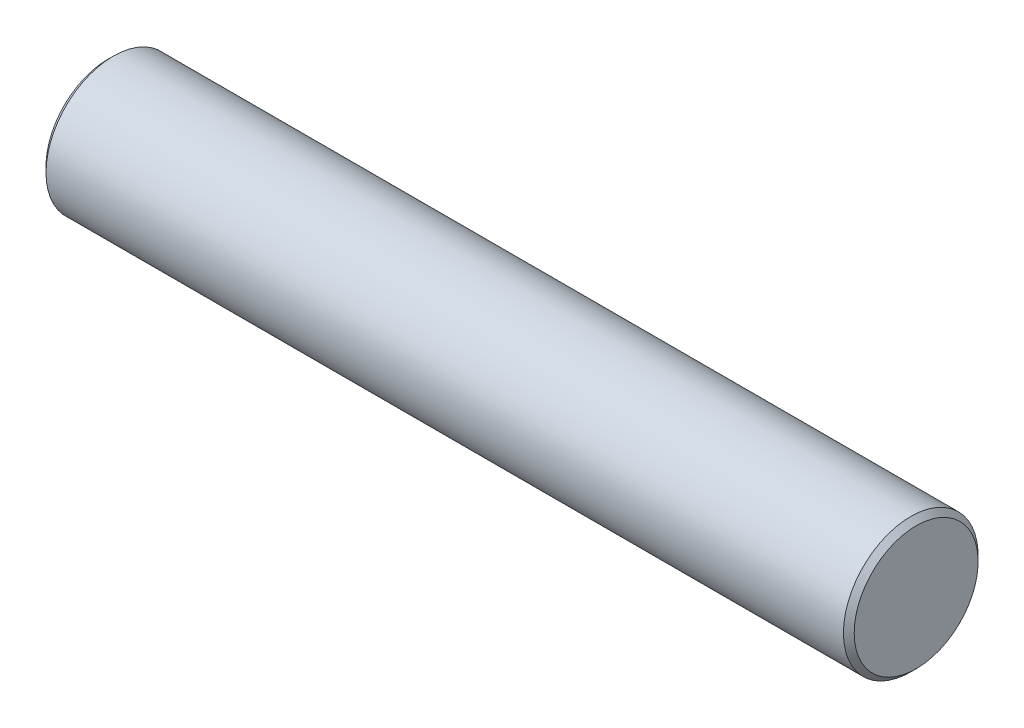
SolidWorks part; units mm, degrees
ref_plane "Front Plane" through (0, 0, 0) normal (0, 0, 1) x (1, 0, 0)
ref_plane "Top Plane" through (0, 0, 0) normal (0, 1, 0) x (1, 0, 0)
ref_plane "Right Plane" through (0, 0, 0) normal (1, 0, 0) x (0, 0, -1)
sketch "Sketch1" plane through (0, 0, 0) normal (0, 0, 1) x (1, 0, 0)
  line L1 (0, 0) -> (30, 0)
  line L2 (0, 0) -> (0, 2.5)
  line L3 (0, 2.5) -> (30, 2.5)
  line L4 (30, 0) -> (30, 2.5)
  dimension "D1" = 30
  dimension "D2" = 2.5
revolve "Revolve1" add sketch "Sketch1" angle 360 about L1
chamfer "Chamfer1" distance 0.2 angle 45 2 edges at (0, 0, 2.5) (30, 0, 2.5)
ref_plane "Plane1" through (15, 0, 0) normal (-1, 0, 0) x (0, 0, 1)
